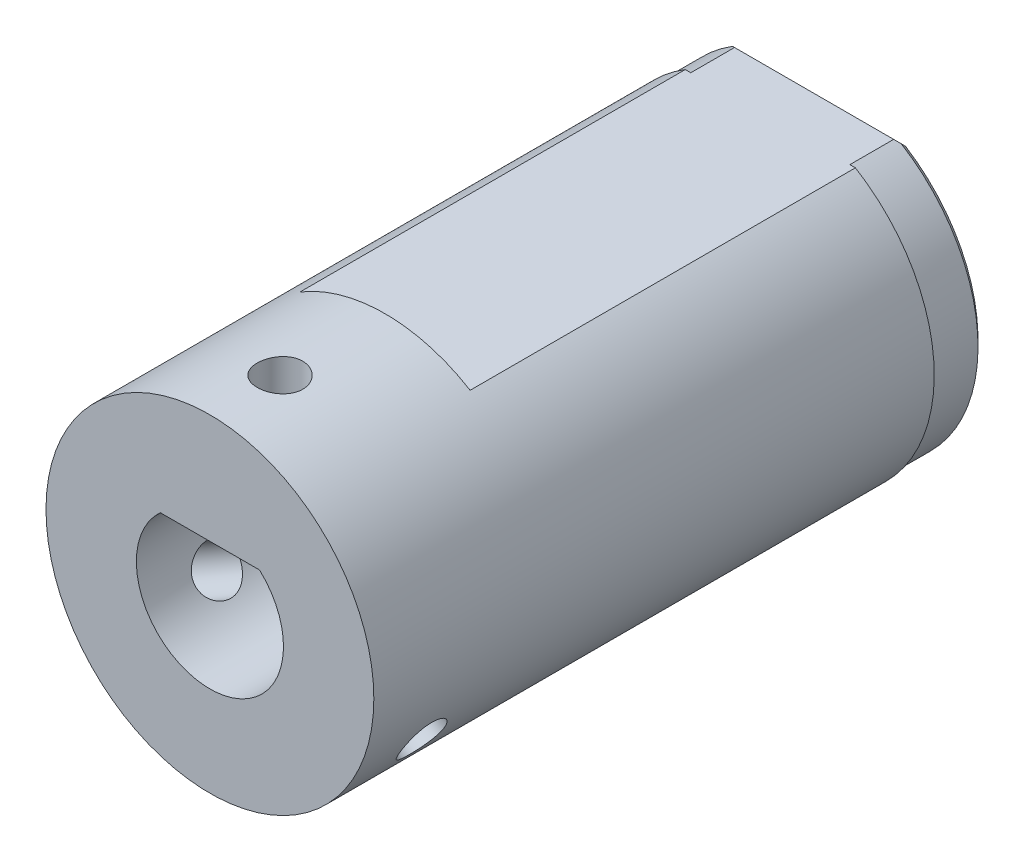
SolidWorks part; units mm, degrees
ref_plane "Спереди" through (0, 0, 0) normal (0, 0, 1) x (1, 0, 0)
ref_plane "Сверху" through (0, 0, 0) normal (0, 1, 0) x (1, 0, 0)
ref_plane "Справа" through (0, 0, 0) normal (1, 0, 0) x (0, 0, -1)
other "Configuration Table"
sketch "Эскиз2" plane through (0, 0, 0) normal (0, 0, 1) x (1, 0, 0)
  circle A0 centre (0, 0) radius 9.36
  circle A1 centre (0, 0) radius 4.2
  dimension "D1" = 18.72
  dimension "D2" = 8.4
extrude "Бобышка-Вытянуть1" add sketch "Эскиз2" along normal blind 35
ref_plane "Плоскость1" through (0, 9.36, 0) normal (0, 1, 0) x (1, 0, 0)
sketch "Эскиз4" plane through (0, 0, 35) normal (0, 0, 1) x (1, 0, 0)
  line L2 (-2.8337, 3.1) -> (2.8337, 3.1)
  arc A2 (-2.8337, 3.1) -> (2.8337, 3.1) centre (0, 0) cw
  circle A3 centre (0, 0) radius 4.2 construction
  point P9 (0, 0)
  dimension "D1" = 3.1
extrude "Бобышка-Вытянуть2" add sketch "Эскиз4" against normal blind 10
sketch "Эскиз3" plane through (0, 9.36, 0) normal (0, 1, 0) x (1, 0, 0)
  line L0 (-9.36, -35) -> (9.36, -35) construction
  circle A0 centre (0, -31) radius 1.3
  dimension "D2" = 2.6
  dimension "D1" = 4
extrude "Вырез-Вытянуть1" cut sketch "Эскиз3" against normal up to surface (5.16 mm away)
pattern_circular "Круговой массив1" count 3 over 360 about axis through (0, 0, 35) along (0, 0, -1) of "Вырез-Вытянуть1"
sketch "Эскиз5" plane through (0, 0, 0) normal (0, 0, -1) x (-1, 0, 0)
  line L0 (-4.859, 8) -> (4.859, 8)
  arc A0 (-4.859, 8) -> (4.859, 8) centre (0, 0) cw
  circle A1 centre (0, 0) radius 9.36 construction
  dimension "D1" = 8
extrude "Вырез-Вытянуть2" cut sketch "Эскиз5" against normal blind 25
chamfer "Фаска1" distance 0.5 angle 45 2 edges at (0, -9.36, 0) (0, 8, 0)
sketch "Эскиз7" plane through (0, 0, 0) normal (0, 0, -1) x (-1, 0, 0)
  circle A0 centre (0, 0) radius 9.5
  circle A1 centre (0, 0) radius 9.2
  dimension "D1" = 18.4
  dimension "D2" = 19
extrude "Вырез-Вытянуть3" cut sketch "Эскиз7" against normal blind 3
